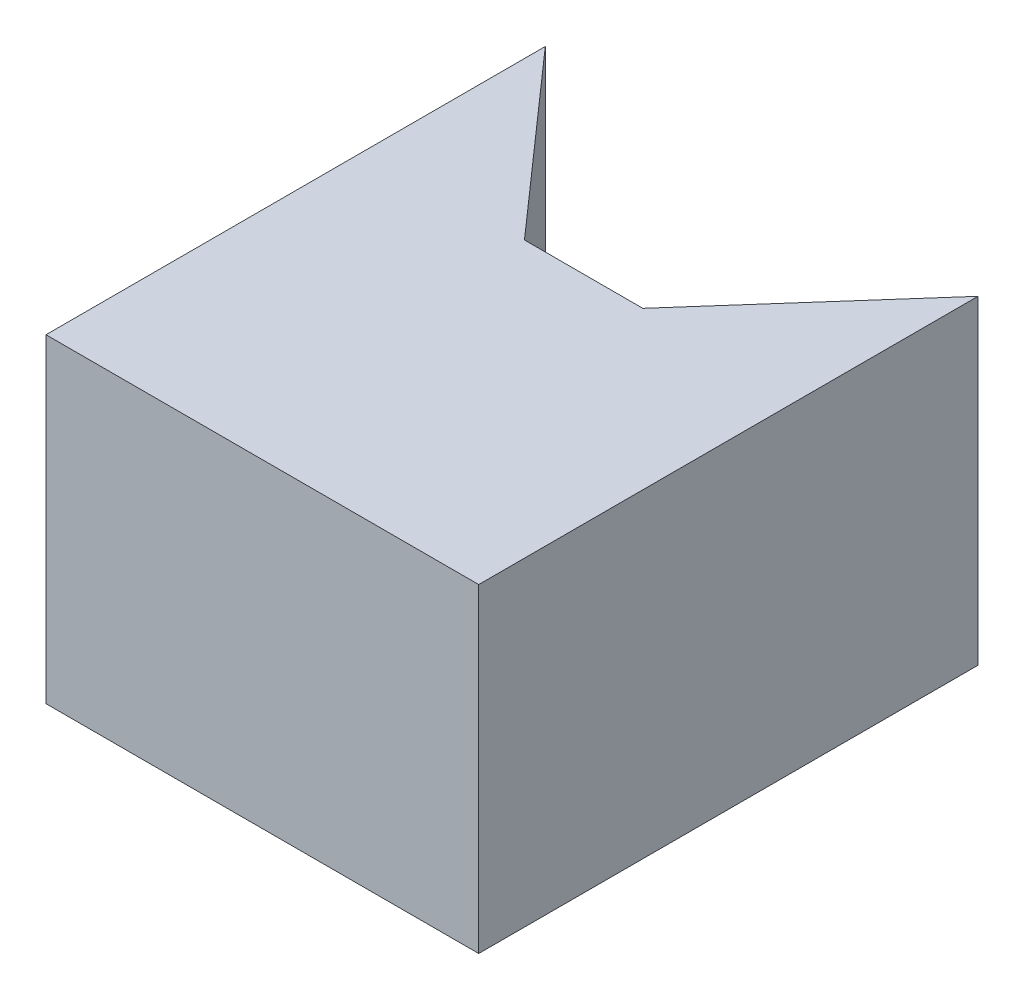
SolidWorks part; units mm, degrees
ref_plane "Front Plane" through (0, 0, 0) normal (0, 0, 1) x (1, 0, 0)
ref_plane "Top Plane" through (0, 0, 0) normal (0, 1, 0) x (1, 0, 0)
ref_plane "Right Plane" through (0, 0, 0) normal (1, 0, 0) x (0, 0, -1)
sketch "Sketch1" plane through (0, 0, 0) normal (0, 1, 0) x (1, 0, 0)
  line L0 (8.89, 0) -> (-8.89, 0)
  line L1 (0, 0) -> (0, -48.26) construction
  line L2 (32.5, -48.26) -> (-32.5, -48.26)
  line L3 (-32.5, -48.26) -> (-32.5, 26.74)
  line L4 (-32.5, 26.74) -> (-8.89, 0)
  line L5 (32.5, 26.74) -> (8.89, 0)
  line L6 (32.5, -48.26) -> (32.5, 26.74)
  point P4 (0, 0)
  point P9 (0, -48.26)
  dimension "D1" = 17.78
  dimension "D3" = 48.26
  dimension "D4" = 65
  dimension "D5" = 75
extrude "Boss-Extrude1" add sketch "Sketch1" along normal blind 48
